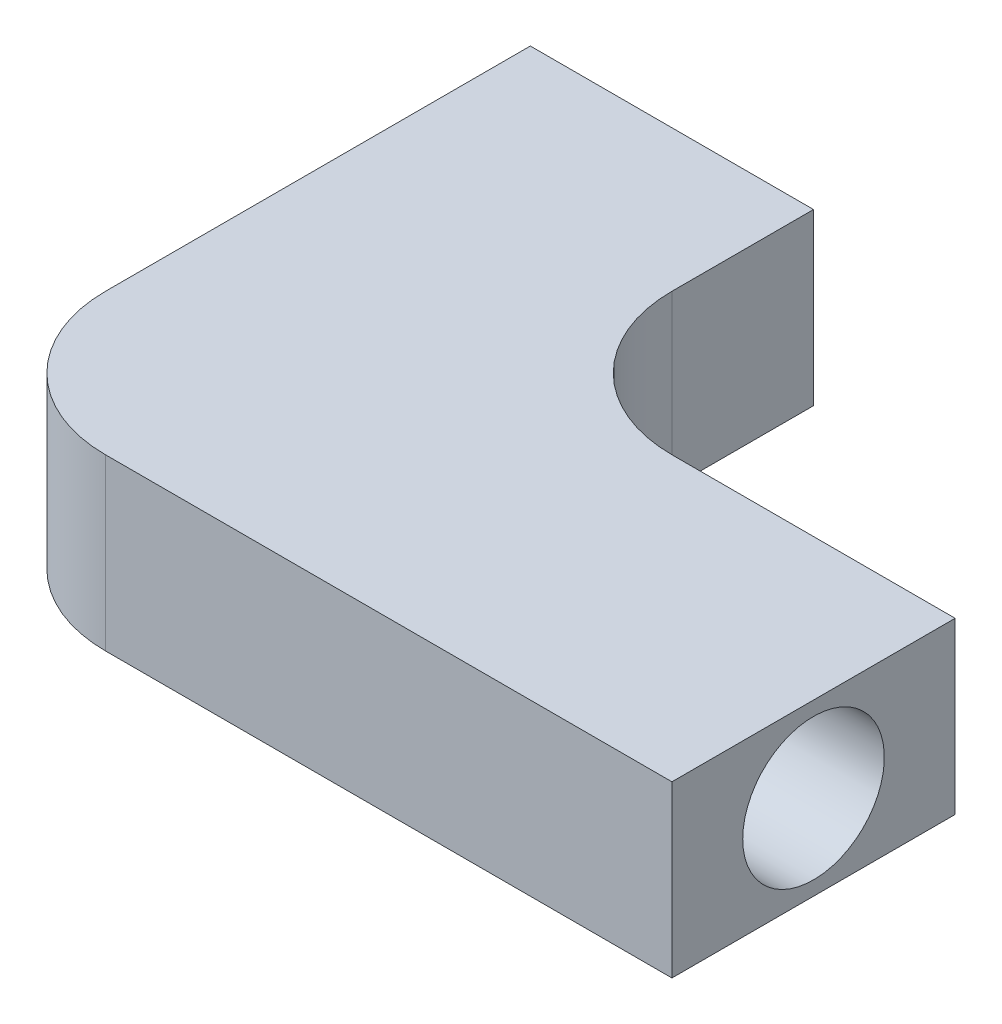
SolidWorks part; units mm, degrees
ref_plane "前视基准面" through (0, 0, 0) normal (0, 0, 1) x (1, 0, 0)
ref_plane "上视基准面" through (0, 0, 0) normal (0, 1, 0) x (1, 0, 0)
ref_plane "右视基准面" through (0, 0, 0) normal (1, 0, 0) x (0, 0, -1)
sketch "草图1" plane through (0, 0, 0) normal (0, 1, 0) x (1, 0, 0)
  line L0 (0, 0) -> (0, -40)
  line L7 (0, -40) -> (50, -40)
  line L8 (50, -40) -> (50, -20)
  line L9 (50, -20) -> (20, -20)
  line L10 (20, -20) -> (20, 0)
  line L11 (20, 0) -> (0, 0)
  point P0 (0, 0)
  dimension "D1" = 20
  dimension "D2" = 20
  dimension "D3" = 40
  dimension "D4" = 30
extrude "凸台-拉伸1" add sketch "草图1" along normal blind 12
sketch "草图2" plane through (0, 0, 0) normal (0, 0, -1) x (-1, 0, 0)
  line L0 (-10, 12) -> (-10, 6) construction
  line L1 (-20, 12) -> (0, 12) construction
  line L2 (0, 6) -> (-10, 6) construction
  line L3 (0, 12) -> (0, 0) construction
  circle A0 centre (-10, 6) radius 5
  dimension "D1" = 10
ref_plane "基准面1" through (0, 6, 0) normal (0, -1, 0) x (-1, 0, 0)
sketch "草图4" plane through (0, 6, 0) normal (0, -1, 0) x (-1, 0, 0)
  line L0 (-10, 3.2705) -> (-10, -20)
  line L2 (-53.0423, -30) -> (-20, -30)
  line L4 (-50, -40) -> (-50, -20) construction
  line L5 (-5, 0) -> (-15, 0) construction
  arc A1 (-20, -30) -> (-10, -20) centre (-20, -20) ccw
  point P2 (-10, 0)
  point P3 (-50, -30)
  point P6 (0, 0)
fillet "圆角2" radius 10 2 edges at (0, 6, 40) (20, 6, 20)
sweep "切除-扫描1" cut profiles "草图2" path "草图4"
